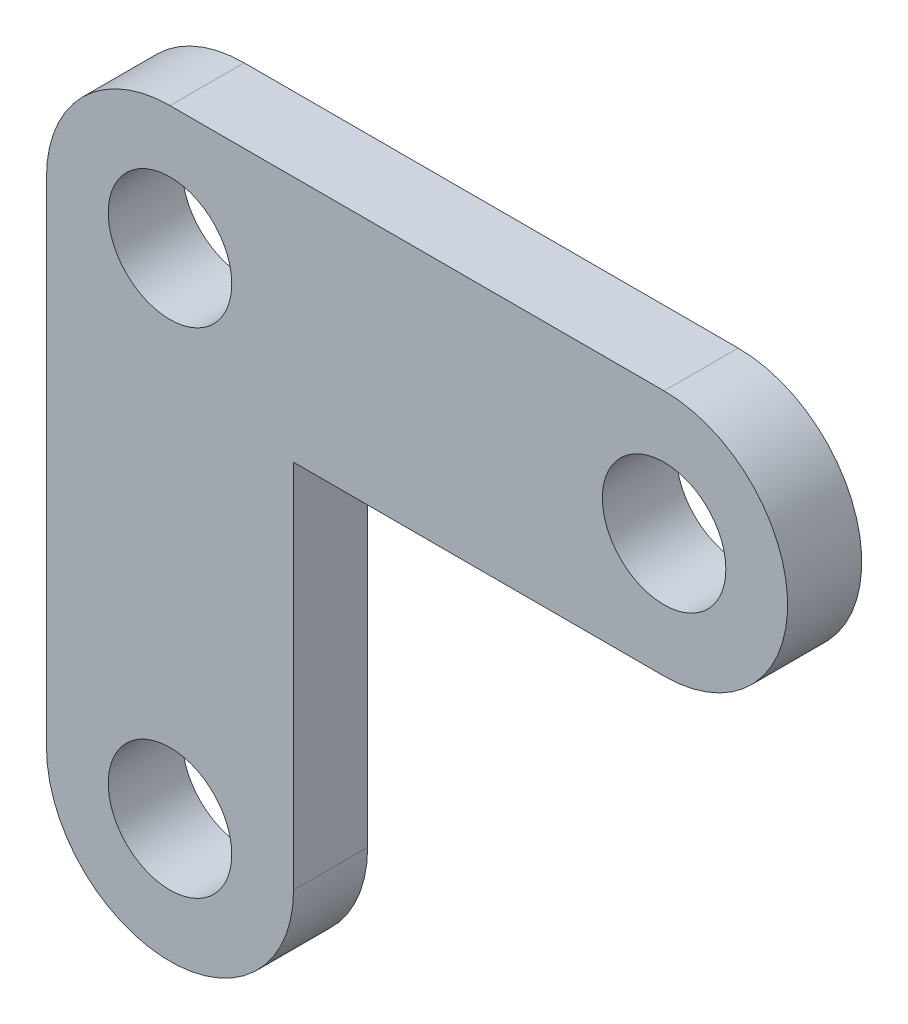
SolidWorks part; units mm, degrees
ref_plane "Front Plane" through (0, 0, 0) normal (0, 0, 1) x (1, 0, 0)
ref_plane "Top Plane" through (0, 0, 0) normal (0, 1, 0) x (1, 0, 0)
ref_plane "Right Plane" through (0, 0, 0) normal (1, 0, 0) x (0, 0, -1)
sketch "Sketch1" plane through (0, 0, 0) normal (0, 0, 1) x (1, 0, 0)
  line L2 (4.0012, 11.6661) -> (4.0012, 31.6661)
  line L3 (4.0012, 31.6661) -> (14.0012, 31.6661)
  line L4 (14.0012, 11.6661) -> (14.0012, 31.6661)
  line L5 (9.0012, 36.6661) -> (29.0012, 36.6661)
  line L6 (9.0012, 36.6661) -> (9.0012, 26.6661)
  line L7 (9.0012, 26.6661) -> (29.0012, 26.6661)
  arc A0 (4.0012, 11.6661) -> (14.0012, 11.6661) centre (9.0012, 11.6661) ccw
  circle A1 centre (9.0012, 11.6661) radius 2.5
  arc A2 (29.0012, 36.6661) -> (29.0012, 26.6661) centre (29.0012, 31.6661) cw
  circle A3 centre (29.0012, 31.6661) radius 2.5
  arc A4 (9.0012, 36.6661) -> (4.0012, 31.6661) centre (9.0012, 31.6661) ccw
  circle A5 centre (9.0012, 31.6661) radius 2.5
  point P20 (14.0012, 26.6661)
  point P27 (14.0012, 26.6661)
  dimension "D3" = 5
  dimension "D7" = 5
  dimension "D9" = 5
  dimension "D1" = 20
  dimension "D2" = 10
  dimension "D4" = 15
  dimension "D5" = 20
  dimension "D6" = 10
  dimension "D8" = 15
extrude "Boss-Extrude1" add sketch "Sketch1" along normal blind 3 contours A5 L3 L4 L7 A2 L5 L6 A3 | A5 L3 L2 A0 L4 L7 L6 A1 | A5 L6 L7 L4 L3 | A5 L6 A4 L3
